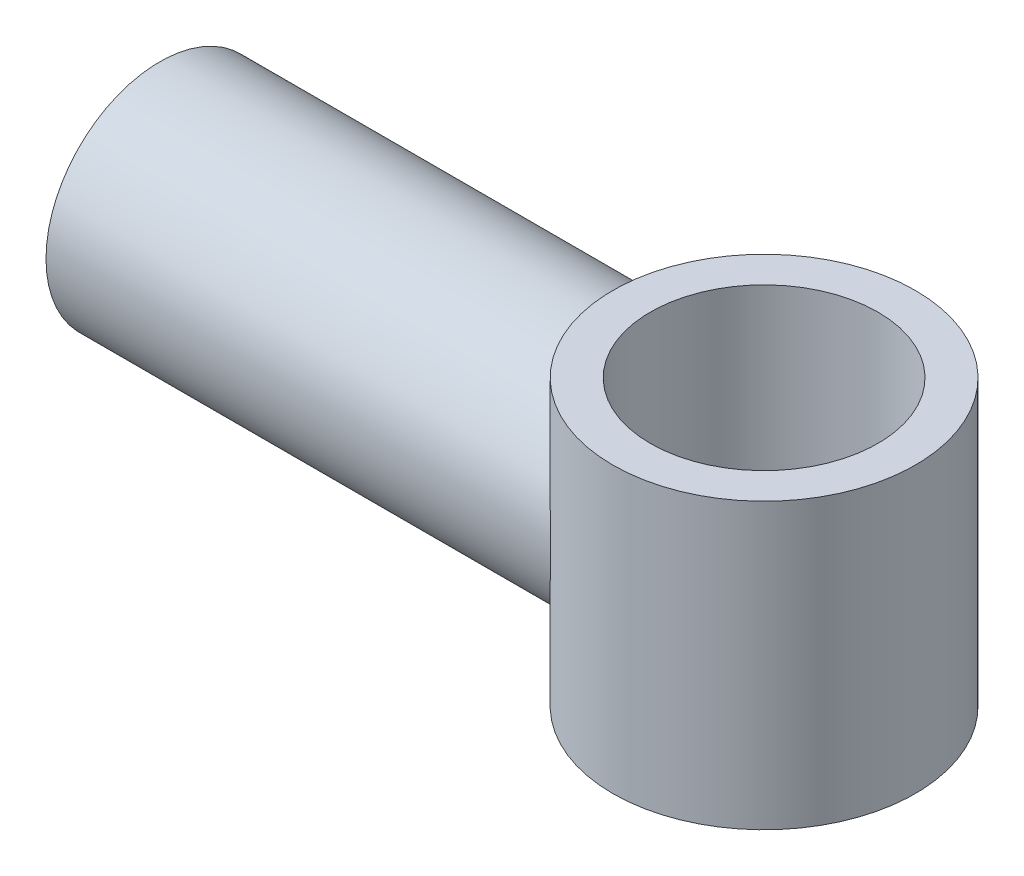
SolidWorks part; units mm, degrees
ref_plane "前视基准面" through (0, 0, 0) normal (0, 0, 1) x (1, 0, 0)
ref_plane "上视基准面" through (0, 0, 0) normal (0, 1, 0) x (1, 0, 0)
ref_plane "右视基准面" through (0, 0, 0) normal (1, 0, 0) x (0, 0, -1)
sketch "草图1" plane through (0, 0, 0) normal (0, 1, 0) x (1, 0, 0)
  circle A0 centre (0, 0) radius 53.1717
  circle A1 centre (0, 0) radius 40
extrude "凸台-拉伸1" add sketch "草图1" against normal blind 50 and the other way blind 50
ref_plane "基准面1" through (-212.4, 0, 0) normal (1, 0, 0) x (0, 0, -1)
sketch "草图2" plane through (-212.4, 0, 0) normal (1, 0, 0) x (0, 0, -1)
  circle A0 centre (0, 0) radius 40
extrude "凸台-拉伸2" add sketch "草图2" along normal up to surface (177.3681 mm away) contours A0
